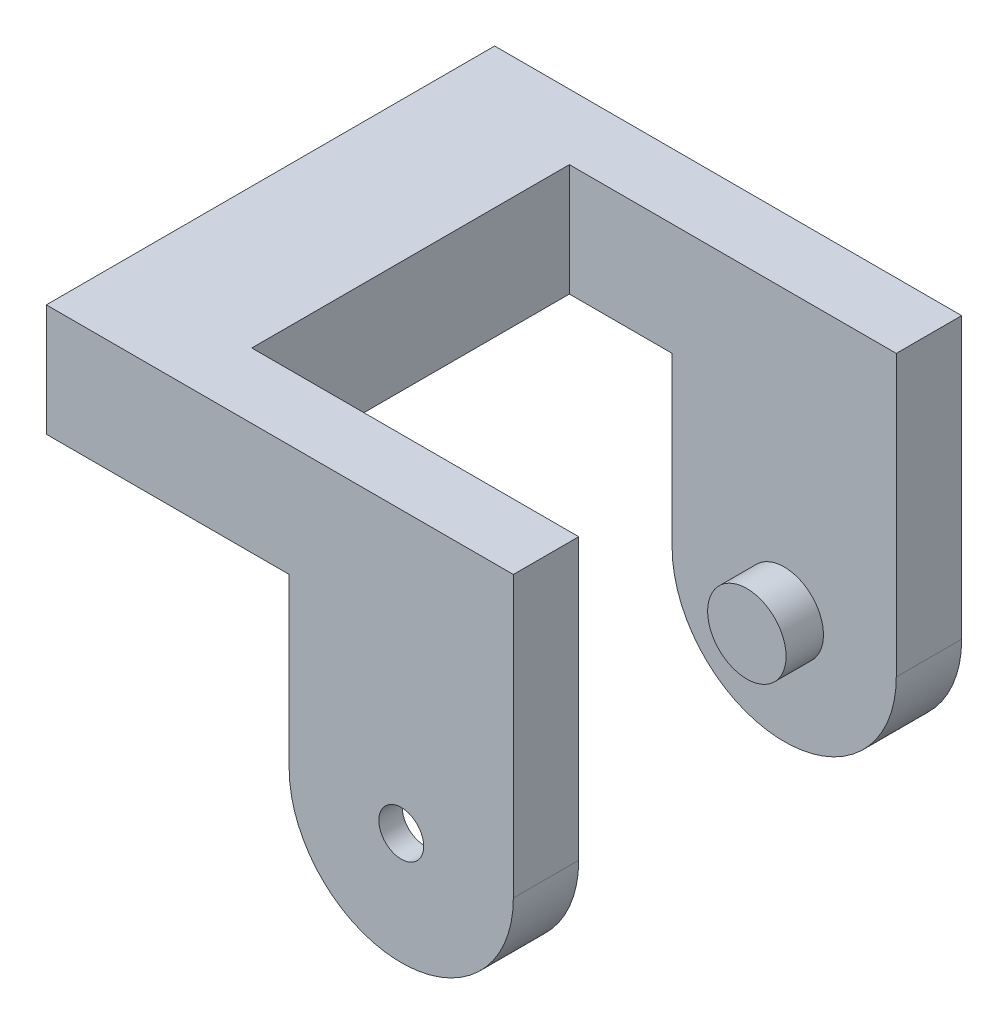
SolidWorks part; units mm, degrees
ref_plane "Front Plane" through (0, 0, 0) normal (0, 0, 1) x (1, 0, 0)
ref_plane "Top Plane" through (0, 0, 0) normal (0, 1, 0) x (1, 0, 0)
ref_plane "Right Plane" through (0, 0, 0) normal (1, 0, 0) x (0, 0, -1)
sketch "Sketch1" plane through (0, 0, 0) normal (0, 0, 1) x (1, 0, 0)
  line L0 (0, 0) -> (0, 30) construction
  line L1 (-12, 0) -> (-12, 30)
  line L2 (12, 0) -> (12, 30)
  line L3 (-12, 30) -> (12, 30)
  line L5 (-12, 30) -> (12, 30)
  line L6 (-12, 30) -> (-12, 26)
  line L7 (-12, 26) -> (12, 26)
  line L8 (12, 30) -> (12, 26)
  circle A0 centre (0, 0) radius 9.5
  arc A2 (-12, 0) -> (12, 0) centre (0, 0) ccw
  arc A3 (12, 30) -> (-12, 30) centre (0, 30) ccw
  point P3 (0, 15)
  dimension "D1" = 19
  dimension "D2" = 30
  dimension "D3" = 12
  dimension "D4" = 4
extrude "Boss-Extrude1" add sketch "Sketch1" against normal blind 48
sketch "Sketch2" plane through (-12, 0, 0) normal (-1, 0, 0) x (0, 0, 1)
  line L0 (-48, -12) -> (0, -12) construction
  line L1 (-7, -12) -> (-41, -12)
  line L2 (-7, -12) -> (-7, 18)
  line L3 (-7, 18) -> (-41, 18)
  line L4 (-41, -12) -> (-41, 18)
  line L5 (-48, 0) -> (-48, 30) construction
  line L6 (0, -12) -> (0, 0) construction
  dimension "D1" = 7
  dimension "D2" = 7
  dimension "D3" = 30
extrude "Cut-Extrude1" cut sketch "Sketch2" against normal through all
sketch "Sketch3" plane through (0, 0, -48) normal (0, 0, -1) x (-1, 0, 0)
  circle A0 centre (0, 0) radius 9.5
  circle A1 centre (0, 0) radius 2.4
  dimension "D1" = 4.8
  dimension "D2" = 19
extrude "Boss-Extrude2" add sketch "Sketch3" against normal blind 2.5
sketch "Sketch4" plane through (0, 0, 0) normal (0, 0, 1) x (1, 0, 0)
  circle A0 centre (0, 0) radius 9.5
  circle A1 centre (0, 0) radius 4.2
  dimension "D1" = 19
  dimension "D2" = 8.4
extrude "Boss-Extrude3" add sketch "Sketch4" against normal blind 7
sketch "Sketch5" plane through (0, 0, 0) normal (0, 0, 1) x (1, 0, 0)
  circle A0 centre (0, 0) radius 4.2
extrude "Boss-Extrude4" add sketch "Sketch5" against normal blind 11
sketch "Sketch6" plane through (0, 0, -48) normal (0, 0, -1) x (-1, 0, 0)
  line L0 (0, 0) -> (30, 0)
  line L1 (-12, 30) -> (12, 30)
  line L2 (-12, 30) -> (-12, 0)
  line L3 (-12, 0) -> (12, 0)
  line L4 (12, 30) -> (12, 0)
  line L5 (-9.5, 0) -> (9.5, 0)
  line L6 (-9.5, 0) -> (-9.5, 30)
  line L7 (-9.5, 30) -> (9.5, 30)
  line L8 (9.5, 0) -> (9.5, 30)
  line L9 (30, 0) -> (0, 0)
  line L10 (0, 0) -> (21.2132, 21.2132)
  line L12 (12, 30) -> (38, 30)
  line L13 (12, 30) -> (12, 18)
  line L14 (12, 18) -> (38, 18)
  line L15 (38, 30) -> (38, 18)
  circle A0 centre (0, 0) radius 12
  circle A3 centre (0, 0) radius 9.5 construction
  dimension "D1" = 50
  dimension "D3" = 45
extrude "Boss-Extrude5" add sketch "Sketch6" against normal blind 48
sketch "Sketch7" plane through (0, 0, 0) normal (0, 0, 1) x (1, 0, 0)
  circle A0 centre (0, 0) radius 2.4
extrude "Cut-Extrude2" cut sketch "Sketch7" against normal through all
sketch "Sketch8" plane through (0, 0, -7) normal (0, 0, -1) x (-1, 0, 0)
  circle A0 centre (0, 0) radius 9.5
extrude "Cut-Extrude3" cut sketch "Sketch8" against normal blind 4.5
sketch "Sketch9" plane through (0, 0, -11) normal (0, 0, -1) x (-1, 0, 0)
  circle A0 centre (0, 0) radius 6.0678
extrude "Cut-Extrude4" cut sketch "Sketch9" against normal blind 4.5
sketch "Sketch10" plane through (0, 0, -45.5) normal (0, 0, 1) x (1, 0, 0)
  circle A0 centre (0, 0) radius 9.5
  dimension "D1" = 19
extrude "Boss-Extrude6" add sketch "Sketch10" along normal blind 4.5
sketch "Sketch11" plane through (0, 0, -41) normal (0, 0, 1) x (1, 0, 0)
  circle A0 centre (0, 0) radius 4.2
extrude "Boss-Extrude7" add sketch "Sketch11" along normal blind 4
sketch "Sketch12" plane through (0, 0, -48) normal (0, 0, -1) x (-1, 0, 0)
  circle A0 centre (0, 0) radius 2.4
extrude "Boss-Extrude8" add sketch "Sketch12" against normal blind 2.5
sketch "Sketch13" plane through (0, 30, 0) normal (0, 1, 0) x (1, 0, 0)
  line L1 (12, 41) -> (-23, 41)
  line L2 (12, 41) -> (12, 7)
  line L3 (12, 7) -> (-23, 7)
  line L4 (-23, 41) -> (-23, 7)
  dimension "D1" = 35
extrude "Cut-Extrude5" cut sketch "Sketch13" against normal blind 14.5
